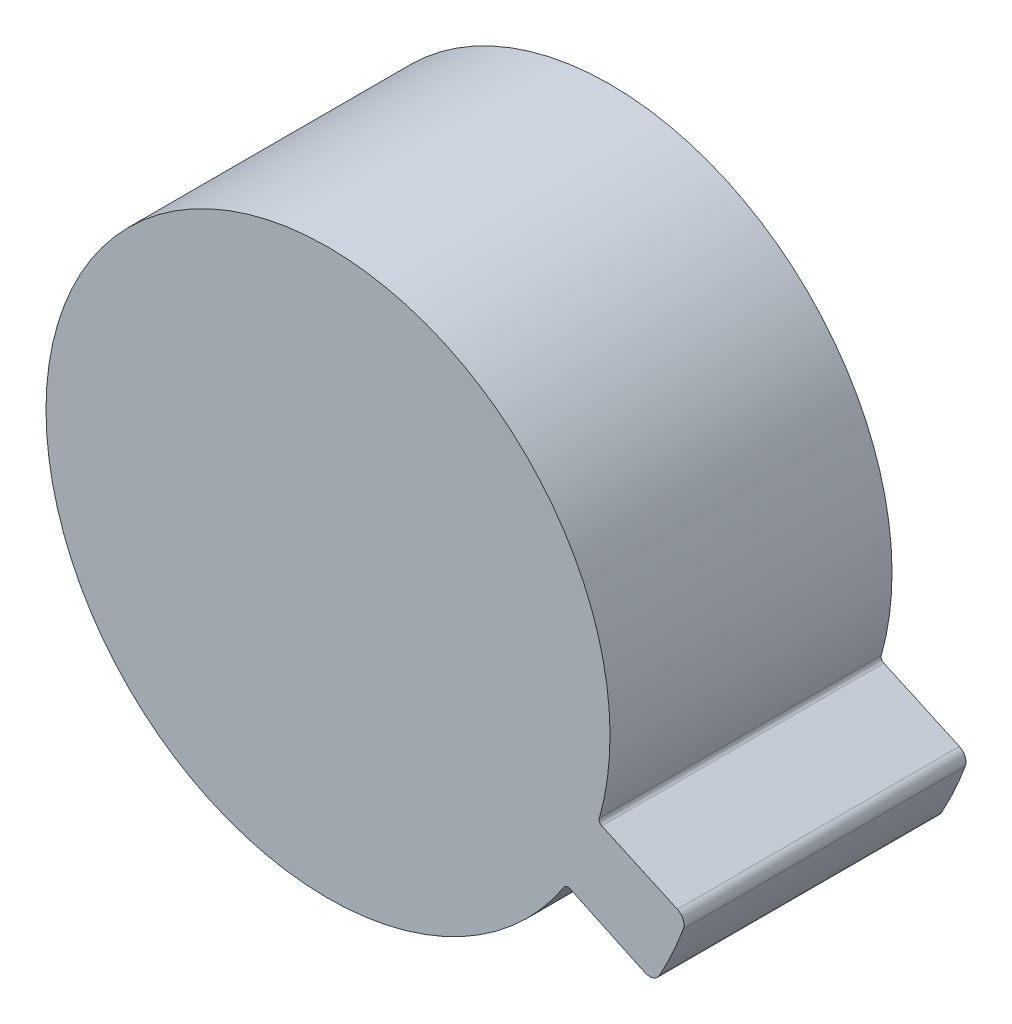
SolidWorks part; units mm, degrees
material "Chêne"
ref_plane "Plan de face" through (0, 0, 0) normal (0, 0, 1) x (1, 0, 0)
ref_plane "Plan de dessus" through (0, 0, 0) normal (0, 1, 0) x (1, 0, 0)
ref_plane "Plan de droite" through (0, 0, 0) normal (1, 0, 0) x (0, 0, -1)
sketch "Esquisse1" plane through (0, 0, 0) normal (0, 0, 1) x (1, 0, 0)
  line L0 (15.4852, -5.1767) -> (12.1342, -3.6507)
  line L1 (14.0407, -8.3254) -> (10.7168, -6.7654)
  arc A0 (12.0247, -3.4141) -> (10.4644, -6.8371) centre (0, 0) ccw
  arc A1 (15.7471, -5.8046) -> (14.6908, -8.1145) centre (0, 0) cw
  arc A2 (15.7471, -5.8046) -> (15.4852, -5.1767) centre (15.278, -5.6317) ccw
  arc A3 (14.0407, -8.3254) -> (14.6908, -8.1145) centre (14.2532, -7.8727) ccw
  arc A5 (12.1342, -3.6507) -> (12.0247, -3.4141) centre (12.2171, -3.4687) cw
  arc A6 (10.7168, -6.7654) -> (10.4644, -6.8371) centre (10.6319, -6.9465) ccw
  point P116 (0, 0)
  point P374 (0, 0)
extrude "Boss.-Extru.3" add sketch "Esquisse1" along normal blind 12.5
